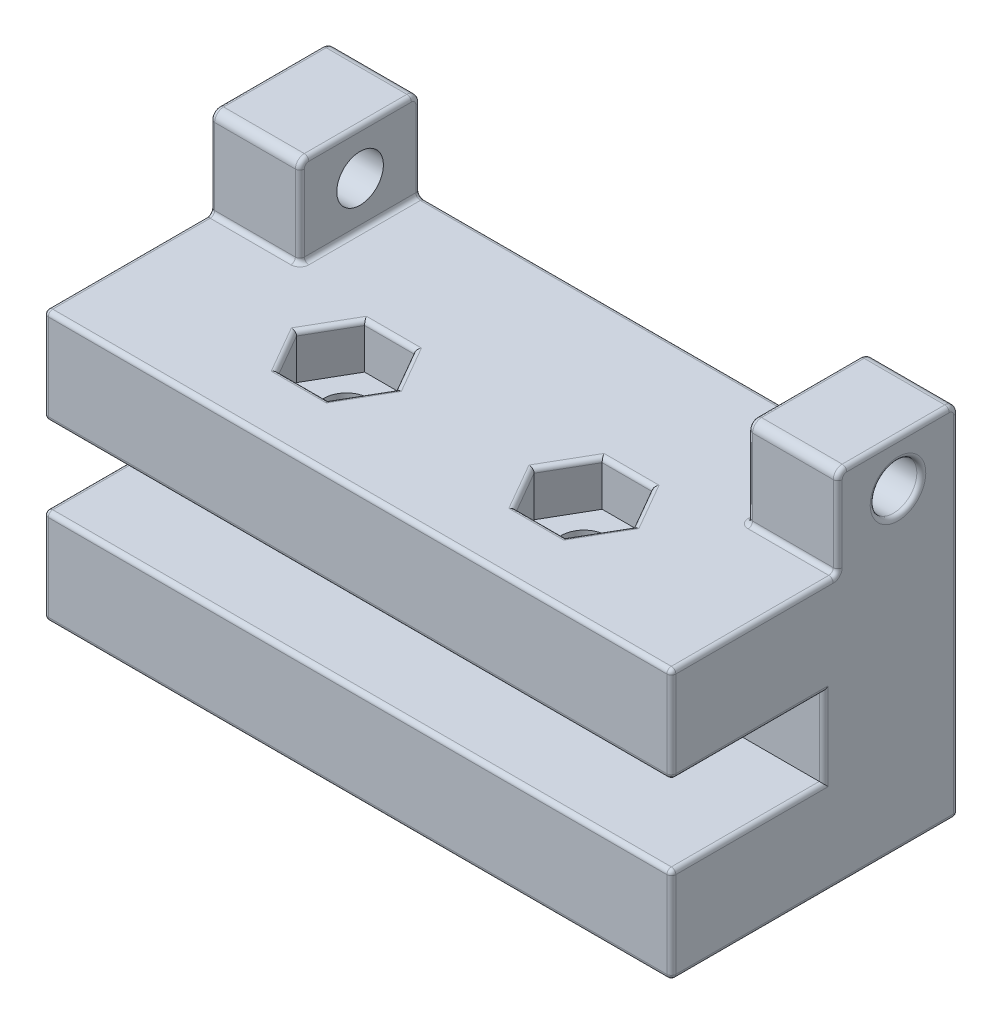
SolidWorks part; units mm, degrees
ref_plane "Front" through (0, 0, 0) normal (0, 0, 1) x (1, 0, 0)
ref_plane "Top" through (0, 0, 0) normal (0, 1, 0) x (1, 0, 0)
ref_plane "Right" through (0, 0, 0) normal (1, 0, 0) x (0, 0, -1)
sketch "Sketch1" plane through (0, 0, 0) normal (0, 0, 1) x (1, 0, 0)
  line L0 (16.5, 0) -> (-16.5, 0) construction
  line L1 (-15, 15) -> (15, 15)
  line L2 (-15, 15) -> (-15, -15)
  line L3 (-15, -15) -> (15, -15)
  line L4 (15, 15) -> (15, -15)
  line L5 (-15, 15) -> (15, -15) construction
  line L6 (-15, -15) -> (15, 15) construction
  line L15 (-5.7238, 7) -> (-3, 4.1)
  line L16 (5.7762, 8) -> (-5.7238, 8)
  line L17 (5.7762, 8) -> (5.7762, 7)
  line L18 (5.7762, 7) -> (-5.7238, 7)
  line L19 (-5.7238, 8) -> (-5.7238, 7)
  line L20 (-3, 4.1) -> (2.9, 4.1)
  line L21 (2.9, 4.1) -> (5.7762, 7)
  line L22 (2.9, -4.1) -> (5.7762, -7)
  line L23 (0, -16.5) -> (0, 16.5) construction
  line L24 (-2.875, 8) -> (3.125, 8)
  line L25 (-2.875, 8) -> (-2.875, 11)
  line L26 (-2.875, 11) -> (3.125, 11)
  line L27 (3.125, 8) -> (3.125, 11)
  line L28 (-3, -4.1) -> (2.9, -4.1)
  line L29 (-5.7238, -7) -> (-3, -4.1)
  line L30 (5.7762, -7) -> (-5.7238, -7)
  line L31 (-5.7238, -8) -> (-5.7238, -7)
  line L32 (5.7762, -8) -> (-5.7238, -8)
  line L33 (5.7762, -8) -> (5.7762, -7)
  line L34 (-2.875, -11) -> (3.125, -11)
  line L35 (3.125, -8) -> (3.125, -11)
  line L36 (-2.875, -8) -> (3.125, -8)
  line L37 (-2.875, -8) -> (-2.875, -11)
  line L39 (-11, 11) -> (11, 11)
  line L40 (-11, 11) -> (-11, -11)
  line L41 (-11, -11) -> (11, -11)
  line L42 (11, 11) -> (11, -11)
  line L43 (-11, 11) -> (11, -11) construction
  line L44 (-11, -11) -> (11, 11) construction
  point P0 (0, 0)
  point P30 (0, 0)
  dimension "D1" = 30
  dimension "D2" = 30
  dimension "D3" = 2.875
  dimension "D4" = 6
  dimension "D5" = 3
  dimension "D6" = 1
  dimension "D7" = 11.5
  dimension "D8" = 3
  dimension "D9" = 2.9
  dimension "D10" = 5.9
extrude "Boss-Extrude1" add sketch "Sketch1" along normal blind 32 contours L4 L1 L2 L3 L39 L42 L41 L34 L40 L26 | L16 L27 L26 L25 | L16 L19 L18 L17 | L20 L21 L18 L15 | L30 L22 L28 L29 | L32 L33 L30 L31 | L32 L37 L34 L35
sketch "Sketch2" plane through (0, 0, 32) normal (0, 0, 1) x (1, 0, 0)
  line L1 (-15, 15) -> (15, 15)
  line L2 (-15, 15) -> (-15, -15)
  line L3 (-15, -15) -> (15, -15)
  line L4 (15, 15) -> (15, -15)
  line L5 (-15, 15) -> (15, -15) construction
  line L6 (-15, -15) -> (15, 15) construction
  point P0 (0, 0)
sketch "Sketch5" plane through (-15, 0, 0) normal (-1, 0, 0) x (0, 0, 1)
  line L0 (0, -16.5) -> (0, 16.5) construction
  line L1 (0, 15) -> (32, 15)
  line L2 (0, 15) -> (0, 4.375)
  line L3 (0, 4.375) -> (32, 4.375)
  line L4 (32, 15) -> (32, 4.375)
  line L5 (32, 15) -> (0, 15) construction
  line L6 (16.5, 0) -> (-16.5, 0) construction
  line L7 (0, -4.375) -> (32, -4.375)
  line L8 (32, -15) -> (32, -4.375)
  line L9 (0, -15) -> (32, -15)
  line L10 (0, -15) -> (0, -4.375)
  line L11 (0, -4.46) -> (32, -4.46)
  line L12 (0, 4.46) -> (32, 4.46)
  line L13 (32, -15) -> (32, 15) construction
  line M12 (32, 15) -> (0, 15)
  line M13 (0, 15) -> (0, -15)
  line M14 (0, -15) -> (32, -15)
  line M16 (32, -15) -> (32, 15)
  dimension "D1" = 10.625
  dimension "D2" = 0.085
extrude "Boss-Extrude3" add sketch "Sketch5" along normal blind 20 contours L12 L2 L3 M16 | L12 L4 M13 M12 | L11 L8 L7 M13 | L11 L10 M14 M16
sketch "Sketch6" plane through (0, 15, 0) normal (0, 1, 0) x (1, 0, 0)
  line L4 (-35, -32) -> (15, -32)
  line L6 (-2.875, 0) -> (-11, 0)
  line L7 (15, -32) -> (15, 0)
  line L8 (15, 0) -> (-35, 0)
  line L9 (-11, 0) -> (-11, -32)
  line L13 (15, -32) -> (15, 0)
  line L14 (15, 0) -> (-35, 0)
  line L18 (-35, -32) -> (15, -32)
  line L23 (-11, -32) -> (-2.875, -32)
  line L24 (-2.875, -32) -> (-2.875, 0)
  line L25 (-2.875, 0) -> (-11, 0)
  line L26 (-11, 0) -> (-11, -32)
  line L27 (-11, -32) -> (-2.875, -32)
  line L28 (-2.875, -32) -> (-2.875, 0)
  line L29 (-35, 0) -> (-35, -32)
  line L30 (-35, 0) -> (-35, -32)
  circle A0 centre (-13.25, -20) radius 2.525
  dimension "D2" = 5.05
  dimension "D3" = 0
  dimension "D4" = 2.25
  dimension "D5" = 20
  dimension "D1" = 0
extrude "Cut-Extrude3" cut sketch "Sketch6" against normal through all contours A0
mirror "Mirror1" about plane through (0, 0, 0) normal (1, 0, 0) of "Cut-Extrude3", "Boss-Extrude3"
sketch "Sketch7" plane through (-15, 0, 0) normal (-1, 0, 0) x (0, 0, 1)
  line L0 (16.5, 0) -> (-16.5, 0) construction
  line L5 (6, 5) -> (41.5776, -5) construction
  line L6 (6, -5) -> (41.5776, 5) construction
  line L7 (32, 4.375) -> (32, 15) construction
  line L9 (32, 15) -> (0, 15) construction
  line L10 (0, 15) -> (0, 4.375) construction
  line L11 (0, 4.375) -> (32, 4.375) construction
  line L12 (0, -4.375) -> (0, -15) construction
  line L13 (0, -15) -> (32, -15) construction
  line L14 (32, -15) -> (32, -4.375) construction
  line L15 (32, -4.375) -> (0, -4.375) construction
  line L16 (32, 4.375) -> (32, 15)
  line L17 (32, 15) -> (0, 15)
  line L18 (0, 15) -> (0, 4.375)
  line L19 (0, 4.375) -> (32, 4.375)
  line L20 (0, -4.375) -> (0, -15)
  line L21 (0, -15) -> (32, -15)
  line L22 (32, -15) -> (32, -4.375)
  line L23 (32, -4.375) -> (0, -4.375)
  line L25 (21.8202, 4.375) -> (32, 4.375)
  line L26 (21.8202, 4.375) -> (21.8202, -4.375)
  line L27 (21.8202, -4.375) -> (32, -4.375)
  line L28 (32, 4.375) -> (32, -4.375)
  line L31 (21.8202, 4.375) -> (21.8202, -4.375)
  line L32 (21.8202, 4.375) -> (21.8202, -4.375)
  line L37 (32, 4.375) -> (21.8202, 4.375)
  line L39 (21.8202, -4.375) -> (32, -4.375)
  line L40 (32, -4.375) -> (32, 4.375)
  line L41 (32, 4.375) -> (21.8202, 4.375)
  line L43 (21.8202, -4.375) -> (32, -4.375)
  line L44 (32, -4.375) -> (32, 4.375)
  line L45 (21.8202, 4.375) -> (21.8202, -4.375)
  point P0 (23.7888, 0)
  dimension "D1" = 0
sketch "Sketch10" plane through (0, 0, 0) normal (1, 0, 0) x (0, 0, -1)
  line L12 (-13.4381, 15) -> (0, 15)
  line L13 (-13.4381, 15) -> (-13.4381, 24)
  line L14 (-12.4381, 25) -> (-1, 25)
  line L15 (0, 15) -> (0, 24)
  line L19 (-32, 15) -> (-32, 4.375)
  line L20 (-32, 4.375) -> (0, 4.375)
  line L21 (0, 4.375) -> (0, 15)
  line L22 (0, 15) -> (-32, 15)
  line L23 (-32, 15) -> (-32, 4.375)
  line L24 (-32, 4.375) -> (0, 4.375)
  line L25 (0, 4.375) -> (0, 15)
  line L26 (0, 15) -> (-32, 15)
  circle A0 centre (-6.7191, 20) radius 2.6
  arc A1 (-1, 25) -> (0, 24) centre (-1, 24) cw
  arc A2 (-13.4381, 24) -> (-12.4381, 25) centre (-12.4381, 24) cw
  point P10 (-6.7191, 25)
  point P14 (0, 25)
  dimension "D2" = 10
  dimension "D4" = 1
  dimension "D5" = 0
  dimension "D3" = 5
  dimension "D1" = 0
sketch "Sketch14" plane through (-35, 0, 0) normal (-1, 0, 0) x (0, 0, 1)
  line L4 (0, 15) -> (0, 4.375)
  line L5 (0, 4.375) -> (32, 4.375)
  line L6 (32, 4.375) -> (32, 15)
  line L7 (32, 15) -> (0, 15)
  line L8 (0, 15) -> (0, 4.375)
  line L9 (0, 4.375) -> (32, 4.375)
  line L10 (32, 4.375) -> (32, 15)
  line L11 (32, 15) -> (0, 15)
  line L12 (12.4381, 25) -> (1, 25)
  line L13 (0, 24) -> (0, 15)
  line L14 (0, 15) -> (13.4381, 15)
  line L15 (13.4381, 15) -> (13.4381, 24)
  line L16 (12.4381, 25) -> (1, 25)
  line L17 (0, 24) -> (0, 15)
  line L18 (0, 15) -> (13.4381, 15)
  line L19 (13.4381, 15) -> (13.4381, 24)
  circle A1 centre (6.7191, 20) radius 2.6
  circle A2 centre (6.7191, 20) radius 2.6
  arc A4 (1, 25) -> (0, 24) centre (1, 24) ccw
  arc A5 (13.4381, 24) -> (12.4381, 25) centre (12.4381, 24) ccw
  arc A6 (1, 25) -> (0, 24) centre (1, 24) ccw
  arc A7 (13.4381, 24) -> (12.4381, 25) centre (12.4381, 24) ccw
  dimension "D1" = 0
  dimension "D2" = 0
  dimension "D3" = 0
extrude "Boss-Extrude9" add sketch "Sketch14" against normal blind 10 contours L19 A7 L16 A6 L17 L11 A2
mirror "Mirror2" about plane through (0, 0, 0) normal (1, 0, 0) of "Boss-Extrude9"
extrude "Cut-Extrude5" cut sketch "Sketch7" against normal through all contours L26 L25 L28 L27
sketch "Sketch18" plane through (-35, 0, 0) normal (-1, 0, 0) x (0, 0, 1)
  line L0 (0, -4.375) -> (32, -4.375) construction
  line L1 (0, 4.375) -> (15, 4.375)
  line L2 (0, 4.375) -> (0, -4.375)
  line L3 (0, -4.375) -> (15, -4.375)
  line L4 (15, 4.375) -> (15, -4.375)
  line L5 (32, 15) -> (32, 4.375) construction
  dimension "D1" = 17
extrude "Boss-Extrude12" add sketch "Sketch18" against normal through all
sketch "Sketch19" plane through (0, 0, 32) normal (0, 0, 1) x (1, 0, 0)
  line L0 (-15, 4.375) -> (-15, -4.375)
  line L1 (13.4894, 4.375) -> (13.4894, -4.375)
  line L2 (-15, 4.375) -> (13.4894, 4.375)
  line L3 (-15, -4.375) -> (13.4894, -4.375)
  line L4 (35, -4.375) -> (11, -4.375) construction
  line L18 (-35, 4.375) -> (-11, 4.375)
  line L19 (-11, 4.375) -> (-11, 11)
  line L20 (-11, 11) -> (-2.875, 11)
  line L21 (-2.875, 11) -> (-2.875, 8)
  line L22 (-2.875, 8) -> (-5.7238, 8)
  line L23 (-5.7238, 8) -> (-5.7238, 7)
  line L24 (-5.7238, 7) -> (-3.2583, 4.375)
  line L26 (3.1727, 4.375) -> (5.7762, 7)
  line L27 (5.7762, 7) -> (5.7762, 8)
  line L28 (5.7762, 8) -> (3.125, 8)
  line L29 (3.125, 8) -> (3.125, 11)
  line L30 (3.125, 11) -> (11, 11)
  line L31 (11, 11) -> (11, 4.375)
  line L32 (11, 4.375) -> (35, 4.375)
  line L33 (35, 4.375) -> (35, 15)
  line L34 (35, 15) -> (-35, 15)
  line L36 (-35, 4.375) -> (-11, 4.375)
  line L37 (-11, 4.375) -> (-11, 11)
  line L38 (-11, 11) -> (-2.875, 11)
  line L39 (-2.875, 11) -> (-2.875, 8)
  line L40 (-2.875, 8) -> (-5.7238, 8)
  line L41 (-5.7238, 8) -> (-5.7238, 7)
  line L42 (-5.7238, 7) -> (-3.2583, 4.375)
  line L44 (3.1727, 4.375) -> (5.7762, 7)
  line L45 (5.7762, 7) -> (5.7762, 8)
  line L46 (5.7762, 8) -> (3.125, 8)
  line L47 (3.125, 8) -> (3.125, 11)
  line L48 (3.125, 11) -> (11, 11)
  line L49 (11, 11) -> (11, 4.375)
  line L50 (11, 4.375) -> (35, 4.375)
  line L52 (35, 15) -> (-35, 15)
  line L54 (-11, -11) -> (-11, -4.375)
  line L55 (-11, -11) -> (-11, -4.375)
  line L56 (-11, -4.375) -> (-35, -4.375)
  line L57 (-11, -4.375) -> (-35, -4.375)
  line L58 (-35, -4.375) -> (-35, -15)
  line L59 (-35, -4.375) -> (-35, -15)
  line L60 (-35, -15) -> (35, -15)
  line L61 (-35, -15) -> (35, -15)
  line L62 (35, -15) -> (35, -4.375)
  line L63 (35, -15) -> (35, -4.375)
  line L64 (35, -4.375) -> (11, -4.375)
  line L65 (35, -4.375) -> (11, -4.375)
  line L67 (11, -4.375) -> (11, -11)
  line L68 (11, -4.375) -> (11, -11)
  line L69 (11, -11) -> (3.125, -11)
  line L70 (11, -11) -> (3.125, -11)
  line L71 (3.125, -11) -> (3.125, -8)
  line L92 (3.125, -11) -> (3.125, -8)
  line L93 (3.125, -8) -> (5.7762, -8)
  line L94 (3.125, -8) -> (5.7762, -8)
  line L95 (5.7762, -8) -> (5.7762, -7)
  line L97 (-3.2583, 4.375) -> (3.1727, 4.375)
  line L98 (-3.2583, 4.375) -> (3.1727, 4.375)
  line L99 (5.7762, -8) -> (5.7762, -7)
  line L102 (5.7762, -7) -> (3.1727, -4.375)
  line L104 (5.7762, -7) -> (3.1727, -4.375)
  line L106 (-3.2583, -4.375) -> (-5.7238, -7)
  line L107 (-3.2583, -4.375) -> (-5.7238, -7)
  line L108 (-5.7238, -7) -> (-5.7238, -8)
  line L109 (-5.7238, -7) -> (-5.7238, -8)
  line L110 (-5.7238, -8) -> (-2.875, -8)
  line L111 (-5.7238, -8) -> (-2.875, -8)
  line L112 (-2.875, -8) -> (-2.875, -11)
  line L113 (-2.875, -8) -> (-2.875, -11)
  line L114 (-2.875, -11) -> (-11, -11)
  line L115 (-2.875, -11) -> (-11, -11)
  line L116 (3.1727, -4.375) -> (-3.2583, -4.375)
  line L117 (3.1727, -4.375) -> (-3.2583, -4.375)
  line L118 (35, 4.375) -> (35, 15)
  line L120 (-35, 15) -> (-35, 4.375)
  line L121 (-35, 15) -> (-35, 4.375)
  point P12 (13.4894, -4.375)
  line M38 (-11, 4.375) -> (-11, 11)
  line M39 (-11, 11) -> (-2.875, 11)
  line M40 (-2.875, 11) -> (-2.875, 8)
  line M41 (-2.875, 8) -> (-5.7238, 8)
  line M42 (-5.7238, 8) -> (-5.7238, 7)
  line M43 (-5.7238, 7) -> (-3.2583, 4.375)
  line M45 (3.1727, 4.375) -> (5.7762, 7)
  line M46 (5.7762, 7) -> (5.7762, 8)
  line M47 (5.7762, 8) -> (3.125, 8)
  line M48 (3.125, 8) -> (3.125, 11)
  line M49 (3.125, 11) -> (11, 11)
  line M50 (11, 11) -> (11, 4.375)
  dimension "D1" = 0
  dimension "D2" = 0
extrude "Boss-Extrude13" add sketch "Sketch19" against normal blind 22.13 contours L115 L113 L111 L109 L107 L3 L55 | L104 L99 L94 L92 L70 L68 L3 | L2 M45 M50 M49 M48 M47 M46 | L2 M38 M43 M42 M41 M40 M39
sketch "Sketch20" plane through (0, 0, 0) normal (0, 0, -1) x (-1, 0, 0)
  line L0 (-11, 4.375) -> (-11, -4.375)
  line L3 (11, 4.375) -> (11, -4.375)
  line L5 (-11, 4.375) -> (11, 4.375)
  line L6 (-11, 4.375) -> (-11, -4.375)
  line L7 (-11, -4.375) -> (11, -4.375)
  line L8 (35, -15) -> (35, 24)
  line L9 (35, 24) -> (25, 24)
  line L10 (25, 24) -> (25, 15)
  line L11 (25, 15) -> (-25, 15)
  line L12 (-25, 15) -> (-25, 24)
  line L13 (-25, 24) -> (-35, 24)
  line L14 (-35, 24) -> (-35, -15)
  line L15 (-35, -15) -> (35, -15)
  line L16 (35, -15) -> (35, 24)
  line L17 (35, 24) -> (25, 24)
  line L18 (25, 24) -> (25, 15)
  line L19 (25, 15) -> (-25, 15)
  line L20 (-25, 15) -> (-25, 24)
  line L21 (-25, 24) -> (-35, 24)
  line L22 (-35, 24) -> (-35, -15)
  line L23 (-35, -15) -> (35, -15)
  line L24 (11, 4.375) -> (11, -4.375)
  line L26 (0, 17.6) -> (0, -17.6) construction
  line L27 (17.6, 0) -> (-17.6, 0) construction
  line L31 (11, 4.375) -> (11, 11) construction
  line L32 (-11, 11) -> (-11, 4.375) construction
  line L33 (11, 4.375) -> (11, 11)
  line L34 (-11, 11) -> (-11, 4.375)
  point P6 (-11, 0)
  point P16 (0, 4.375)
  line M18 (-3.1727, 4.375) -> (-11, 4.375)
  line M24 (3.2583, -4.375) -> (11, -4.375)
  line M31 (-11, -4.375) -> (-3.1727, -4.375)
  line M39 (11, 4.375) -> (3.2583, 4.375)
  dimension "D2" = 8.75
  dimension "D1" = 0
extrude "Cut-Extrude6" cut sketch "Sketch20" against normal up to vertex (9.87 mm away) contours L7 L3 L5 L0 M31 M24 M39 M18
sketch "Sketch21" plane through (0, 0, 0) normal (0, 1, 0) x (1, 0, 0)
  line L4 (35, -32) -> (35, -13.4381)
  line L6 (35, -32) -> (35, -13.4381)
  line L11 (25, 0) -> (-25, 0)
  line L13 (35, -13.4381) -> (25, -13.4381)
  line L14 (35, -13.4381) -> (25, -13.4381)
  line L15 (-35, -32) -> (35, -32)
  line L19 (25, 0) -> (-25, 0)
  line L23 (-35, -32) -> (35, -32)
  line L24 (25, -13.4381) -> (25, 0)
  line L25 (25, -13.4381) -> (25, 0)
  line L26 (-25, 0) -> (-25, -13.4381)
  line L27 (-25, 0) -> (-25, -13.4381)
  line L28 (-25, -13.4381) -> (-35, -13.4381)
  line L29 (-25, -13.4381) -> (-35, -13.4381)
  line L30 (-35, -13.4381) -> (-35, -32)
  line L31 (-35, -13.4381) -> (-35, -32)
  circle A2 centre (-11.75, -20) radius 10
  circle A3 centre (-11.75, -20) radius 2.525
  dimension "D2" = 20
  dimension "D1" = 0
extrude "Cut-Extrude7" cut sketch "Sketch21" against normal up to surface and the other way up to surface contours A2 A3
mirror "Mirror3" about plane through (0, 0, 0) normal (1, 0, 0) of "Cut-Extrude7"
sketch "Sketch23" plane through (0, 15, 0) normal (0, 1, 0) x (1, 0, 0)
  line L0 (-11, -18.8541) -> (-11, -21.1459) construction
  line L1 (-11, -18.8541) -> (-11, -21.1459)
  line L8 (35, -32) -> (35, -13.4381)
  line L9 (35, -13.4381) -> (25, -13.4381)
  line L10 (25, -13.4381) -> (25, 0)
  line L11 (25, 0) -> (-25, 0)
  line L12 (-25, 0) -> (-25, -13.4381)
  line L13 (-25, -13.4381) -> (-35, -13.4381)
  line L14 (-35, -13.4381) -> (-35, -32)
  line L15 (-35, -32) -> (35, -32)
  line L16 (35, -32) -> (35, -13.4381)
  line L17 (35, -13.4381) -> (25, -13.4381)
  line L18 (25, -13.4381) -> (25, 0)
  line L19 (25, 0) -> (-25, 0)
  line L20 (-25, 0) -> (-25, -13.4381)
  line L21 (-25, -13.4381) -> (-35, -13.4381)
  line L22 (-35, -13.4381) -> (-35, -32)
  line L23 (-35, -32) -> (35, -32)
  circle A0 centre (13.25, -20) radius 2.525 construction
  circle A1 centre (-13.25, -20) radius 2.525 construction
  circle A2 centre (13.25, -20) radius 2.525
  circle A3 centre (-13.25, -20) radius 2.525
  point P16 (0, 0)
  circle M9 centre (13.25, -20) radius 2.525
  circle M10 centre (-13.25, -20) radius 2.525
  dimension "D1" = 0
extrude "Cut-Extrude9" cut sketch "Sketch23" against normal through all contours L1 M10 | L1 M10 | M9
sketch "Sketch24" plane through (0, 0, 32) normal (0, 0, 1) x (1, 0, 0)
  line L0 (35, -4.375) -> (-35, -4.375) construction
  line L5 (-20.4103, 4.375) -> (20.4103, 4.375)
  line L7 (-20.4103, 4.375) -> (-20.4103, -4.375)
  line L8 (-20.4103, -4.375) -> (20.4103, -4.375)
  line L9 (20.4103, 4.375) -> (20.4103, -4.375)
  line L10 (35, -4.375) -> (20.4103, -4.375) construction
extrude "Cut-Extrude10" cut sketch "Sketch24" against normal through all contours L7 L5 L9 L8
fillet "Fillet2" radius 0.5 80 edges at (0, 15, 32) (0, 4.375, 32) (-35, 9.6875, 32) (-35, 15, 22.7191) (-35, 4.5, 0) (0, -4.375, 32) (-35, -15, 16) (-35, -9.6875, 32) (-13.25, 15, 22.525) (35, 9.6875, 32) (35, 4.5, 0) (35, 15, 22.7191) (35, -9.6875, 32) (35, -15, 16) (13.25, 15, 22.525) (0, 15, 0) (-25, 19.5, 13.4381) (-30, 15, 13.4381) (-25, 19.5, 0) (-25, 24.7071, 0.2929) (-25, 25, 6.7191) (-35, 17.4, 6.7191) (-25, 24.7071, 13.1452) (-25, 15, 6.7191) (-35, 19.5, 13.4381) (-35, 24.7071, 13.1452) (-35, 25, 6.7191) (-35, 24.7071, 0.2929) (0, -15, 32) (35, 19.5, 13.4381) (30, 15, 13.4381) (35, 24.7071, 13.1452) (35, 25, 6.7191) (35, 24.7071, 0.2929) (25, 15, 6.7191) (25, 19.5, 13.4381) (25, 24.7071, 13.1452) (25, 25, 6.7191) (25, 24.7071, 0.2929) (25, 19.5, 0) (35, 17.4, 6.7191) (-11, 7.6875, 0) (35, -4.375, 23.5) (-6.9375, -11, 0) (35, 4.375, 23.5) (-35, -4.375, 23.5) (-35, 4.375, 23.5) (4.4745, -5.6875, 0) (-2.875, -9.5, 0) (4.4745, 5.6875, 0) (-4.2994, -8, 0) (-5.7238, -7.5, 0) (-4.491, -5.6875, 0) (35, 0, 15) (-35, 0, 15) (5.7762, -7.5, 0) (4.4506, -8, 0) (3.125, -9.5, 0) (7.0625, -11, 0) (11, 7.6875, 0) (7.0625, 11, 0) (3.125, 9.5, 0) (4.4506, 8, 0) (5.7762, 7.5, 0) (-4.491, 5.6875, 0) (-5.7238, 7.5, 0) (-4.2994, 8, 0) (-2.875, 9.5, 0) (-6.9375, 11, 0) (0, -15, 0) (-0.0428, -4.375, 0) (-0.0428, 4.375, 0) (11, -7.6875, 0) (-11, -7.6875, 0) (15.7051, 4.375, 0) (20.4103, 0, 0) (-20.4103, 0, 0) (15.7051, -4.375, 0) (-15.7051, -4.375, 0) (-15.7051, 4.375, 0)
sketch "Sketch29" plane through (0, 15, 0) normal (0, 1, 0) x (1, 0, 0)
  line L1 (-10.4719, -24.8119) -> (-7.6938, -20)
  line L2 (-7.6938, -20) -> (-10.4719, -15.1881)
  line L3 (-10.4719, -15.1881) -> (-16.0281, -15.1881)
  line L4 (-16.0281, -15.1881) -> (-18.8063, -20)
  line L5 (-18.8063, -20) -> (-16.0281, -24.8119)
  line L6 (-16.0281, -24.8119) -> (-10.4719, -24.8119)
  line L8 (-25.5, -13.9381) -> (-34.5, -13.9381)
  line L9 (-34.5, -13.9381) -> (-34.5, -31.5)
  line L10 (-34.5, -31.5) -> (34.5, -31.5)
  line L11 (34.5, -31.5) -> (34.5, -13.9381)
  line L12 (34.5, -13.9381) -> (25.5, -13.9381)
  line L13 (24.5, -12.9381) -> (24.5, -0.5)
  line L14 (24.5, -0.5) -> (-24.5, -0.5)
  line L15 (-24.5, -0.5) -> (-24.5, -12.9381)
  line L16 (-25.5, -13.9381) -> (-34.5, -13.9381)
  line L17 (-34.5, -13.9381) -> (-34.5, -31.5)
  line L18 (-34.5, -31.5) -> (34.5, -31.5)
  line L19 (34.5, -31.5) -> (34.5, -13.9381)
  line L20 (34.5, -13.9381) -> (25.5, -13.9381)
  line L21 (24.5, -12.9381) -> (24.5, -0.5)
  line L22 (24.5, -0.5) -> (-24.5, -0.5)
  line L23 (-24.5, -0.5) -> (-24.5, -12.9381)
  circle A0 centre (-13.25, -20) radius 3.025 construction
  circle A1 centre (-13.25, -20) radius 2.525 construction
  arc A2 (-25.5, -13.9381) -> (-24.5, -12.9381) centre (-25.5, -12.9381) ccw
  arc A3 (24.5, -12.9381) -> (25.5, -13.9381) centre (25.5, -12.9381) ccw
  arc A4 (-25.5, -13.9381) -> (-24.5, -12.9381) centre (-25.5, -12.9381) ccw
  arc A5 (24.5, -12.9381) -> (25.5, -13.9381) centre (25.5, -12.9381) ccw
  circle A6 centre (-13.25, -20) radius 3.025
  circle A7 centre (-13.25, -20) radius 2.525
  circle A8 centre (-13.25, -20) radius 4.8119 construction
  circle M18 centre (-13.25, -20) radius 3.025
  dimension "D2" = 5.5562
  dimension "D1" = 0
extrude "Cut-Extrude11" cut sketch "Sketch29" against normal blind 5 contours L5 L6 L1 L2 L3 L4 M18 | A7 M18 | A6
fillet "Fillet3" radius 0.5 6 edges at (-13.25, 15, 24.8119) (-9.0828, 15, 22.4059) (-9.0828, 15, 17.5941) (-13.25, 15, 15.1881) (-17.4172, 15, 17.5941) (-17.4172, 15, 22.4059)
mirror "Mirror4" about plane through (0, 0, 0) normal (1, 0, 0) of "Cut-Extrude11", "Fillet3"
fillet "Fillet4" radius 1 2 edges at (20.4103, 0, 15) (-20.4103, 0, 15)
